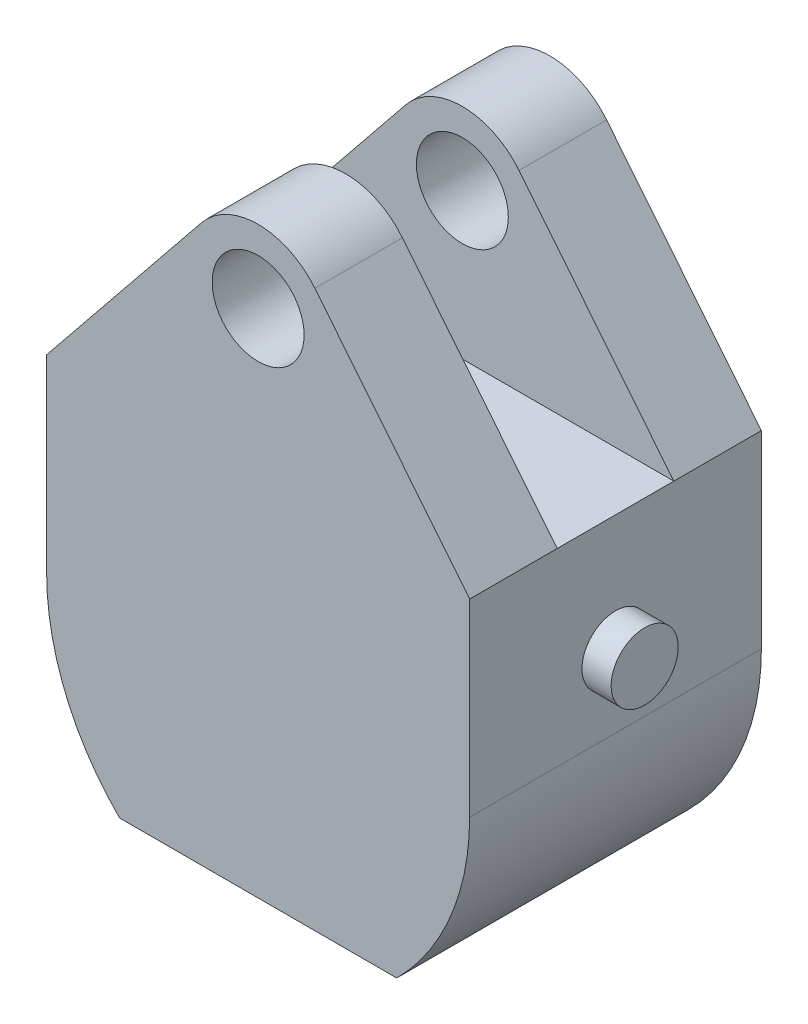
SolidWorks part; units mm, degrees
ref_plane "Front Plane" through (0, 0, 0) normal (0, 0, 1) x (1, 0, 0)
ref_plane "Top Plane" through (0, 0, 0) normal (0, 1, 0) x (1, 0, 0)
ref_plane "Right Plane" through (0, 0, 0) normal (1, 0, 0) x (0, 0, -1)
sketch "Sketch1" plane through (0, 0, 0) normal (0, 0, 1) x (1, 0, 0)
  line L1 (0, 0) -> (29, 0)
  line L2 (0, 0) -> (0, -40)
  line L3 (0, -40) -> (29, -40)
  line L4 (29, 0) -> (29, -40)
  dimension "D1" = 29
  dimension "D2" = 40
extrude "Boss-Extrude1" add sketch "Sketch1" along normal blind 20
sketch "Sketch2" plane through (0, 0, 0) normal (0, 1, 0) x (1, 0, 0)
  line L0 (0, -20) -> (0, 0) construction
  line L1 (0, -6) -> (29, -6)
  line L2 (0, -6) -> (0, -14)
  line L3 (0, -14) -> (29, -14)
  line L4 (29, -6) -> (29, -14)
  line L5 (29, -20) -> (29, 0) construction
  line L6 (-55, 0) -> (55, 0) construction
  dimension "D1" = 8
  dimension "D2" = 6
extrude "Cut-Extrude1" cut sketch "Sketch2" against normal blind 15
sketch "Sketch3" plane through (0, 0, 20) normal (0, 0, 1) x (1, 0, 0)
  line L0 (14.5, 0) -> (14.5, -10) construction
  line L1 (29, 0) -> (0, 0) construction
  line L2 (0, -15) -> (29, -15) construction
  line L3 (29, -40) -> (29, 0) construction
  line L4 (0, 0) -> (0, -40) construction
  line L5 (0, -15) -> (10.6097, -1.8591)
  line L6 (29, -15) -> (18.3903, -1.8591)
  line L7 (0, -35) -> (29, -35) construction
  line L8 (0, -40) -> (29, -40) construction
  line L9 (0, -35) -> (5, -40)
  line L10 (29, -35) -> (24, -40)
  circle A0 centre (14.5, -5) radius 5
  circle A1 centre (14.5, -5) radius 3.15
  line M5 (0, 0) -> (0, -40)
  line M6 (0, -40) -> (29, -40)
  line M7 (29, -40) -> (29, 0)
  line M8 (29, 0) -> (0, 0)
  dimension "D2" = 15
  dimension "D3" = 6.3
  dimension "D1" = 10
  dimension "D4" = 5
  dimension "D5" = 5
  dimension "D6" = 5
extrude "Cut-Extrude2" cut sketch "Sketch3" against normal blind 30 contours A0 L5 M8 M5 | A0 L6 M7 M8 | L9 M5 M6 | L10 M7 M6 | A1
fillet "Fillet1" radius 17 2 edges at (0, -35, 10) (29, -35, 10)
sketch "Sketch4" plane through (29, 0, 0) normal (1, 0, 0) x (0, 0, -1)
  line L1 (-14, -15) -> (-6, -15) construction
  line L2 (-10, -15) -> (-10, -23) construction
  circle A0 centre (-10, -23) radius 2.3
  dimension "D1" = 4.6
  dimension "D2" = 8
extrude "Boss-Extrude2" add sketch "Sketch4" along normal blind 2 and the other way blind 32
